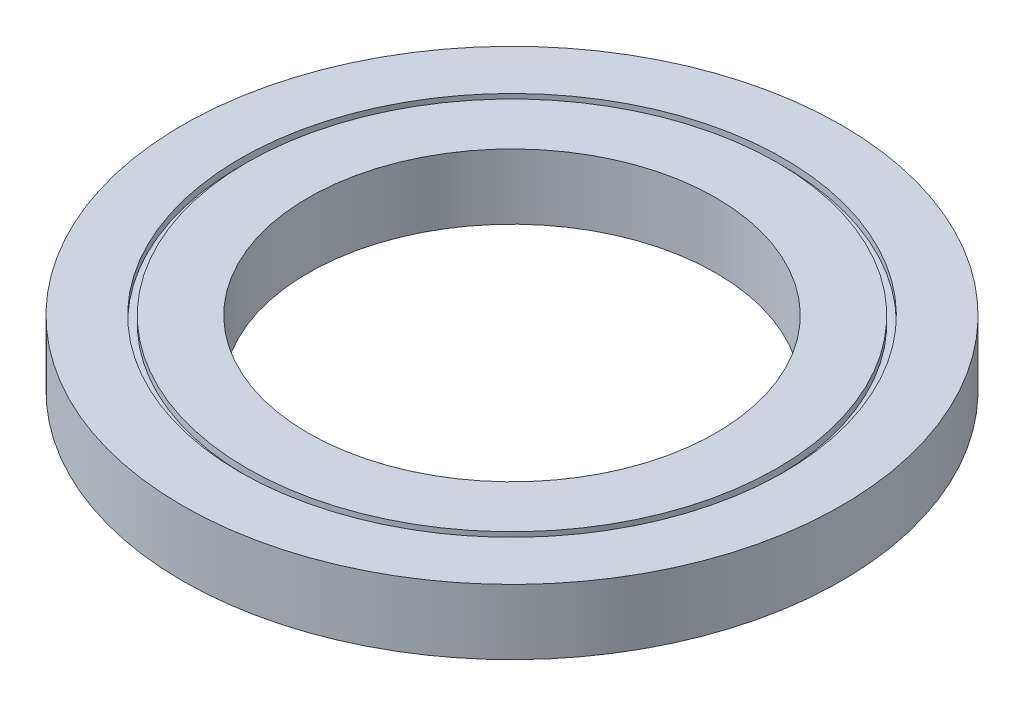
SolidWorks part; units mm, degrees
ref_plane "Front Plane" through (0, 0, 0) normal (0, 0, 1) x (1, 0, 0)
ref_plane "Top Plane" through (0, 0, 0) normal (0, 1, 0) x (1, 0, 0)
ref_plane "Right Plane" through (0, 0, 0) normal (1, 0, 0) x (0, 0, -1)
sketch "Sketch1" plane through (0, 0, 0) normal (0, 1, 0) x (1, 0, 0)
  circle A0 centre (0, 0) radius 48.5
  circle A1 centre (0, 0) radius 30
  dimension "D1" = 97
  dimension "D2" = 60
extrude "Boss-Extrude1" add sketch "Sketch1" along normal blind 9.59
sketch "Sketch2" plane through (0, 0, 0) normal (0, 1, 0) x (1, 0, 0)
  circle A0 centre (0, 0) radius 40
  circle A1 centre (0, 0) radius 39
  dimension "D1" = 80
  dimension "D2" = 1
extrude "Cut-Extrude1" cut sketch "Sketch2" along normal blind 1
sketch "Sketch3" plane through (0, 9.59, 0) normal (0, 1, 0) x (1, 0, 0)
  circle A0 centre (0, 0) radius 40
  circle A1 centre (0, 0) radius 39
extrude "Cut-Extrude2" cut sketch "Sketch3" against normal blind 1
